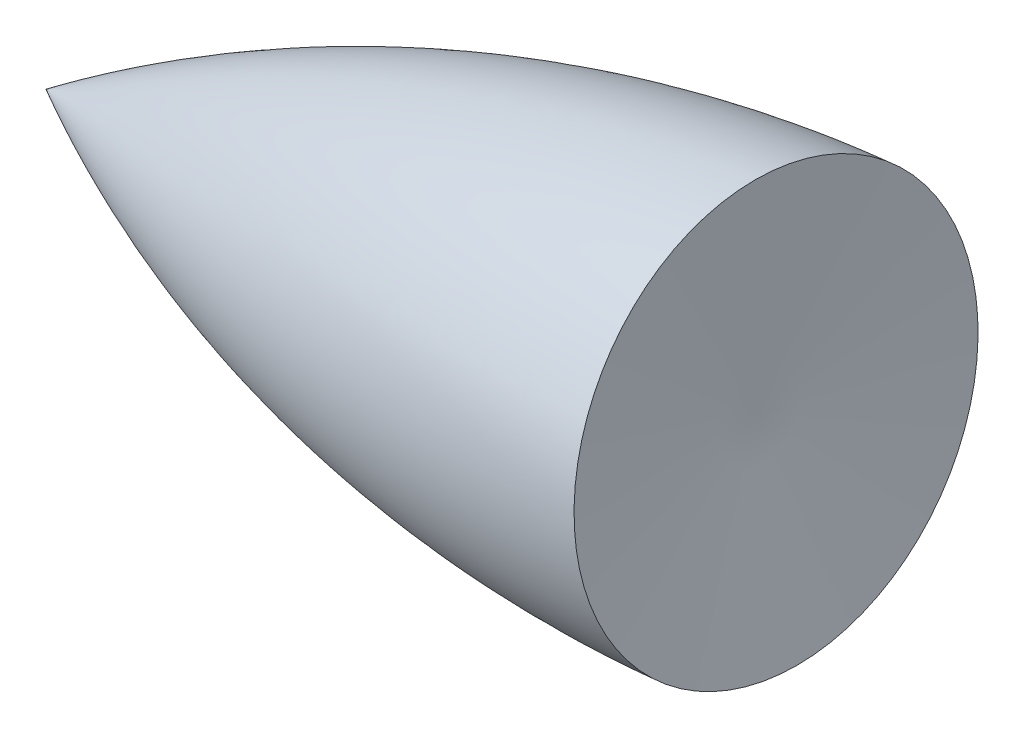
SolidWorks part; units mm, degrees
ref_plane "Front Plane" through (0, 0, 0) normal (0, 0, 1) x (1, 0, 0)
ref_plane "Top Plane" through (0, 0, 0) normal (0, 1, 0) x (1, 0, 0)
ref_plane "Right Plane" through (0, 0, 0) normal (1, 0, 0) x (0, 0, -1)
sketch "Sketch1" plane through (0, 0, 0) normal (0, 0, 1) x (1, 0, 0)
  line L0 (-272.6714, -46.0143) -> (63.9952, -46.0143) construction
  line L1 (18.1409, 25.8423) -> (89.3355, 33.2853)
  line L2 (89.3355, 33.2853) -> (89.3355, 53.5671)
  arc A0 (18.1409, 25.8423) -> (89.3355, 53.5671) centre (104.9715, -91.8574) cw
revolve "Revolve2" add sketch "Sketch1" angle 360 about L1
